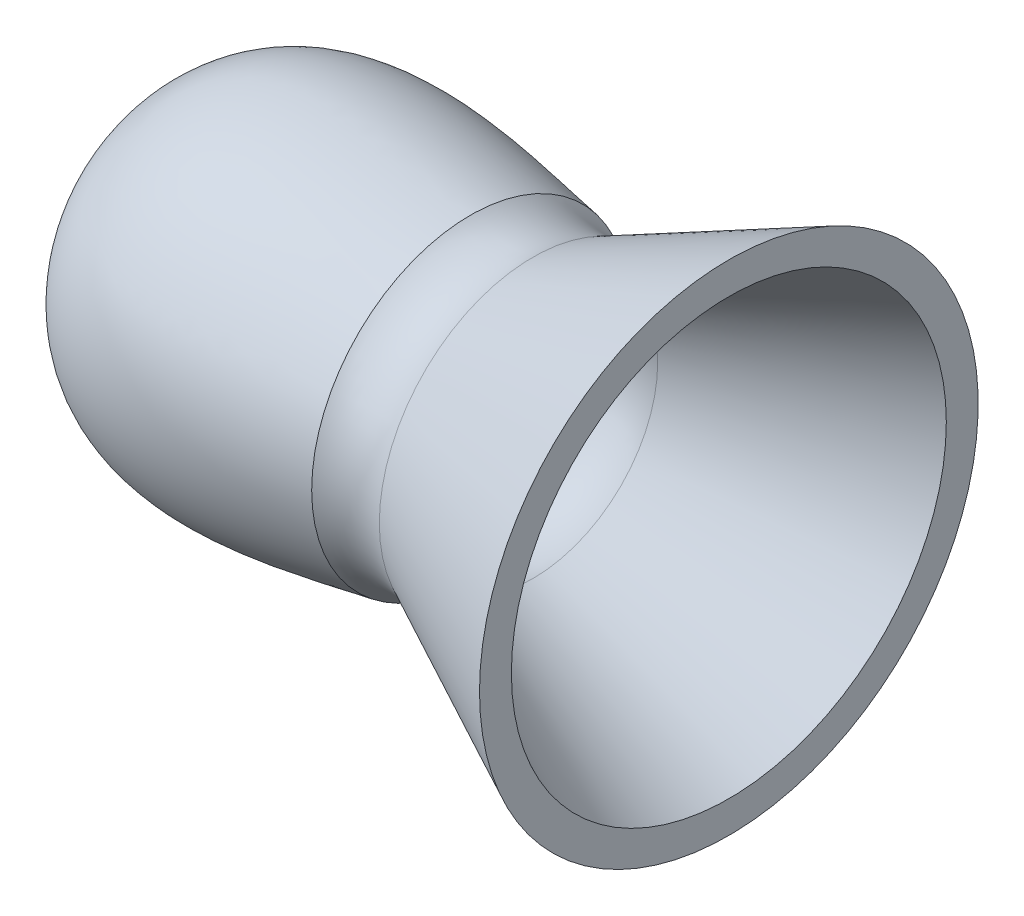
SolidWorks part; units mm, degrees
ref_plane "Front Plane" through (0, 0, 0) normal (0, 0, 1) x (1, 0, 0)
ref_plane "Top Plane" through (0, 0, 0) normal (0, 1, 0) x (1, 0, 0)
ref_plane "Right Plane" through (0, 0, 0) normal (1, 0, 0) x (0, 0, -1)
sketch "Sketch1" plane through (0, 0, 0) normal (0, 0, 1) x (1, 0, 0)
  line L0 (129.4549, 14.9106) -> (197.3947, 48.1005)
  line L1 (129.4549, 4.8643) -> (197.3947, 37.0439)
  line L2 (197.3947, 37.0439) -> (197.3947, 48.1005)
  line L3 (8.1347, -5.816) -> (0, 0)
  line L4 (129.4549, -38.3936) -> (197.3947, -38.3936) construction
  arc A0 (107.7441, 16.6641) -> (129.4549, 14.9106) centre (120.0788, 34.1035) ccw
  arc A1 (106.0451, 6.8095) -> (129.4549, 4.8643) centre (119.2928, 24.4037) ccw
  spline S0 degree 3 poles (0, 0) (24.5387, 34.3215) (72.0069, 22.8254) (107.7441, 16.6641) knots 0 0 0 0 1 1 1 1
  spline S1 degree 1 poles (8.1347, -5.816) (106.0451, 6.8095) knots 0 0 1 1 construction
  spline S2 degree 3 poles (8.1347, -5.816) (8.4493, -5.3761) (9.0987, -4.4994) (10.4116, -2.8484) (12.1087, -0.9281) (14.2244, 1.1524) (17.1559, 3.6561) (21.0333, 6.3183) (26.0597, 8.8662) (31.4819, 10.8294) (39.2333, 12.7213) (49.8336, 13.8051) (63.5845, 13.3867) (75.481, 11.9874) (85.0258, 10.5048) (92.1463, 9.2819) (98.0026, 8.2306) (102.6284, 7.4051) (104.9025, 7.0065) (106.0451, 6.8095) knots 0 0 0 0 0.015625 0.03125 0.0625 0.09375 0.125 0.1875 0.25 0.3125 0.375 0.5 0.625 0.75 0.8125 0.875 0.9375 0.96875 1 1 1 1
  dimension "D1" = 10
revolve "Revolve3" add sketch "Sketch1" angle 360 about L4
